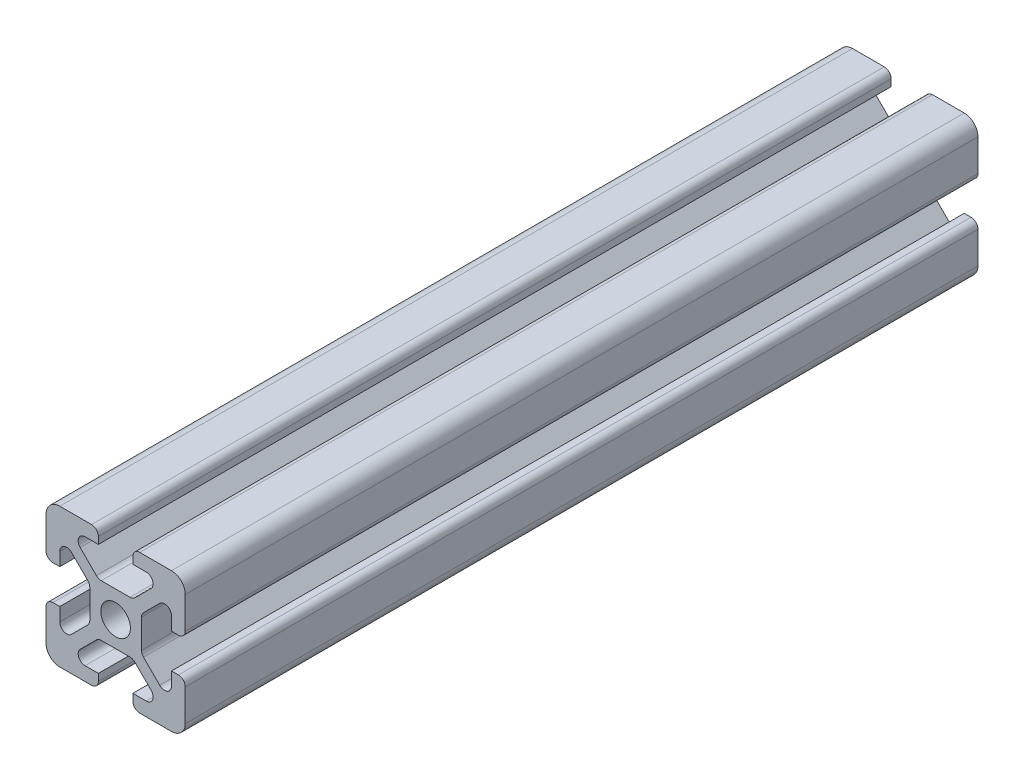
SolidWorks part; units mm, degrees
ref_plane "Front Plane" through (0, 0, 0) normal (0, 0, 1) x (1, 0, 0)
ref_plane "Top Plane" through (0, 0, 0) normal (0, 1, 0) x (1, 0, 0)
ref_plane "Right Plane" through (0, 0, 0) normal (1, 0, 0) x (0, 0, -1)
sketch "Sketch1" plane through (0, 0, 0) normal (0, 0, 1) x (1, 0, 0)
  line L0 (10.1, 10) -> (10.1, 0.1) construction
  line L1 (2, 0) -> (6.6, 0)
  line L2 (0, 2) -> (0, 6.6)
  line L3 (2, 20.2) -> (6.6, 20.2)
  line L4 (20.2, 2) -> (20.2, 6.6)
  line L5 (10.1, 10) -> (0, 10) construction
  line L6 (7.6, 19.2) -> (7.6, 18.2)
  line L7 (7.6, 18.2) -> (5.6642, 18.2)
  line L8 (4.9571, 16.4929) -> (7.3071, 14.1429)
  line L9 (8.0142, 13.85) -> (12.1858, 13.85)
  line L10 (12.8929, 14.1429) -> (15.2429, 16.4929)
  line L11 (14.5358, 18.2) -> (12.6, 18.2)
  line L12 (12.6, 18.2) -> (12.6, 19.2)
  line L13 (-250.157, -110.88) -> (53.1764, -110.88) construction
  line L14 (13.6, 20.2) -> (18.2, 20.2)
  line L15 (19.2, 12.6) -> (18.2, 12.6)
  line L16 (18.2, 12.6) -> (18.2, 14.5358)
  line L17 (16.4929, 15.2429) -> (14.1429, 12.8929)
  line L18 (13.85, 12.1858) -> (13.85, 8.0142)
  line L19 (14.1429, 7.3071) -> (16.4929, 4.9571)
  line L20 (18.2, 5.6642) -> (18.2, 7.6)
  line L21 (18.2, 7.6) -> (19.2, 7.6)
  line L22 (12.6, 1) -> (12.6, 2)
  line L23 (12.6, 2) -> (14.5358, 2)
  line L24 (15.2429, 3.7071) -> (12.8929, 6.0571)
  line L25 (12.1858, 6.35) -> (8.0142, 6.35)
  line L26 (7.3071, 6.0571) -> (4.9571, 3.7071)
  line L27 (5.6642, 2) -> (7.6, 2)
  line L28 (7.6, 2) -> (7.6, 1)
  line L29 (1, 7.6) -> (2, 7.6)
  line L30 (2, 7.6) -> (2, 5.6642)
  line L31 (3.7071, 4.9571) -> (6.0571, 7.3071)
  line L32 (6.35, 8.0142) -> (6.35, 12.1858)
  line L33 (6.0571, 12.8929) -> (3.7071, 15.2429)
  line L34 (2, 14.5358) -> (2, 12.6)
  line L35 (2, 12.6) -> (1, 12.6)
  line L36 (20.2, 13.6) -> (20.2, 18.2)
  line L37 (13.6, 0) -> (18.2, 0)
  line L38 (0, 13.6) -> (0, 18.2)
  circle A0 centre (10.1, 10) radius 2.15
  arc A1 (12.8929, 14.1429) -> (12.1858, 13.85) centre (12.1858, 14.85) cw
  arc A2 (8.0142, 13.85) -> (7.3071, 14.1429) centre (8.0142, 14.85) cw
  arc A3 (15.2429, 16.4929) -> (14.5358, 18.2) centre (14.5358, 17.2) ccw
  arc A4 (5.6642, 18.2) -> (4.9571, 16.4929) centre (5.6642, 17.2) ccw
  arc A5 (2, 0) -> (0, 2) centre (2, 2) cw
  arc A6 (18.2, 0) -> (20.2, 2) centre (18.2, 2) ccw
  arc A7 (20.2, 18.2) -> (18.2, 20.2) centre (18.2, 18.2) ccw
  arc A8 (2, 20.2) -> (0, 18.2) centre (2, 18.2) ccw
  arc A9 (18.2, 14.5358) -> (16.4929, 15.2429) centre (17.2, 14.5358) ccw
  arc A10 (13.85, 12.1858) -> (14.1429, 12.8929) centre (14.85, 12.1858) cw
  arc A11 (14.1429, 7.3071) -> (13.85, 8.0142) centre (14.85, 8.0142) cw
  arc A12 (16.4929, 4.9571) -> (18.2, 5.6642) centre (17.2, 5.6642) ccw
  arc A13 (14.5358, 2) -> (15.2429, 3.7071) centre (14.5358, 3) ccw
  arc A14 (12.1858, 6.35) -> (12.8929, 6.0571) centre (12.1858, 5.35) cw
  arc A15 (7.3071, 6.0571) -> (8.0142, 6.35) centre (8.0142, 5.35) cw
  arc A16 (4.9571, 3.7071) -> (5.6642, 2) centre (5.6642, 3) ccw
  arc A17 (2, 5.6642) -> (3.7071, 4.9571) centre (3, 5.6642) ccw
  arc A18 (6.35, 8.0142) -> (6.0571, 7.3071) centre (5.35, 8.0142) cw
  arc A19 (6.0571, 12.8929) -> (6.35, 12.1858) centre (5.35, 12.1858) cw
  arc A20 (3.7071, 15.2429) -> (2, 14.5358) centre (3, 14.5358) ccw
  arc A21 (20.2, 13.6) -> (19.2, 12.6) centre (19.2, 13.6) cw
  arc A22 (20.2, 6.6) -> (19.2, 7.6) centre (19.2, 6.6) ccw
  arc A23 (13.6, 0) -> (12.6, 1) centre (13.6, 1) cw
  arc A24 (7.6, 1) -> (6.6, 0) centre (6.6, 1) cw
  arc A25 (1, 7.6) -> (0, 6.6) centre (1, 6.6) ccw
  arc A26 (1, 12.6) -> (0, 13.6) centre (1, 13.6) cw
  arc A27 (7.6, 19.2) -> (6.6, 20.2) centre (6.6, 19.2) ccw
  arc A28 (13.6, 20.2) -> (12.6, 19.2) centre (13.6, 19.2) ccw
  point P21 (12.6, 13.85)
  point P24 (7.6, 13.85)
  point P31 (0, 0)
  point P36 (20.2, 20.2)
  point P39 (0, 20.2)
  point P91 (10.1, 10.1)
  point P105 (12.6, 20.2)
  dimension "D3" = 4.3
  dimension "D9" = 1
  dimension "D10" = 2
  dimension "D13" = 1
  dimension "D1" = 20.2
  dimension "D2" = 10.1
  dimension "D4" = 5
  dimension "D5" = 2.5
  dimension "D6" = 6.35
  dimension "D7" = 2
  dimension "D8" = 45
  dimension "D12" = 10
  dimension "D14" = 20.2
  dimension "D15" = 7.6
  dimension "D16" = 6.35
  dimension "D11" = 4
extrude "Boss-Extrude1" add sketch "Sketch1" along normal blind 115
